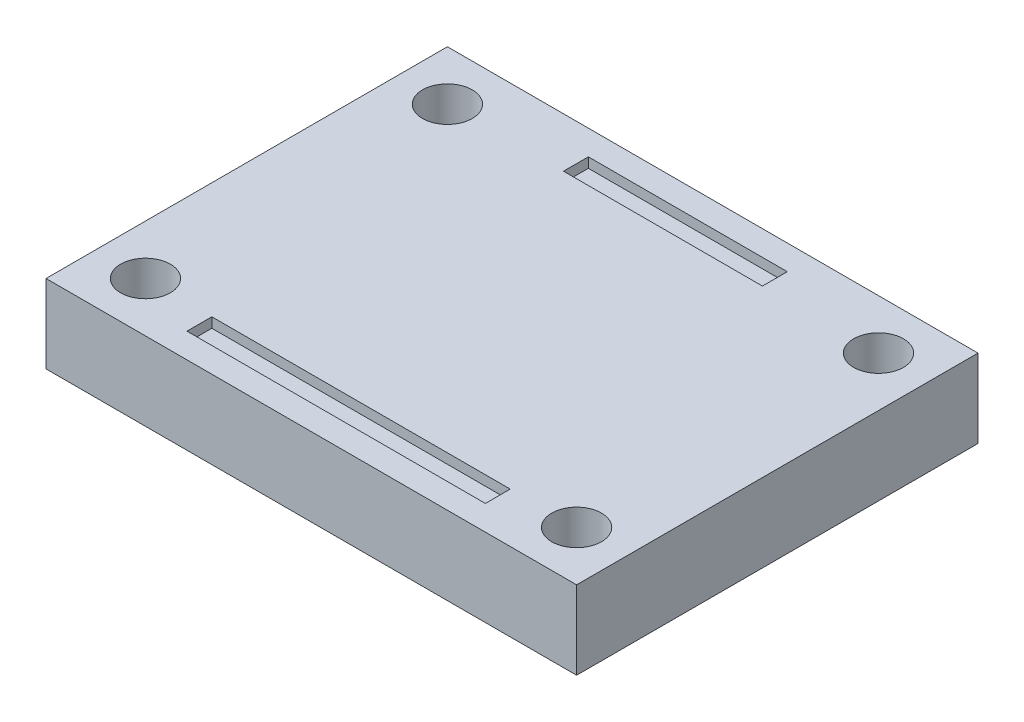
SolidWorks part; units mm, degrees
ref_plane "Front Plane" through (0, 0, 0) normal (0, 0, 1) x (1, 0, 0)
ref_plane "Top Plane" through (0, 0, 0) normal (0, 1, 0) x (1, 0, 0)
ref_plane "Right Plane" through (0, 0, 0) normal (1, 0, 0) x (0, 0, -1)
sketch "Sketch1" plane through (0, 0, 0) normal (0, 1, 0) x (1, 0, 0)
  line L0 (0, 0) -> (0, 20.5)
  line L1 (0, 0) -> (27.1, 0)
  line L2 (0, 20.5) -> (27.1, 20.5)
  line L3 (27.1, 0) -> (27.1, 20.5)
  dimension "D1" = 27.1
  dimension "D2" = 20.5
extrude "Boss-Extrude1" add sketch "Sketch1" along normal blind 4 contours L1 L3 L2 L0
sketch "Sketch3" plane through (0, 4, 0) normal (0, 1, 0) x (1, 0, 0)
  line L0 (0, 0) -> (0, 20.5) construction
  line L1 (13.55, 28.5431) -> (13.55, -9.9219) construction
  line L2 (-7.4225, 10.25) -> (32.0223, 10.25) construction
  line L3 (0, 20.5) -> (27.1, 20.5) construction
  circle A0 centre (2.54, 17.96) radius 1.27
  circle A1 centre (2.54, 2.54) radius 1.27
  circle A2 centre (24.56, 2.54) radius 1.27
  circle A3 centre (24.56, 17.96) radius 1.27
  dimension "D1" = 2.54
  dimension "D2" = 2.54
  dimension "D3" = 2.54
sketch "Sketch2" plane through (0, 4, 0) normal (0, 1, 0) x (1, 0, 0)
  line L0 (27.1, 0) -> (27.1, 20.5) construction
  line L1 (0, 20.5) -> (27.1, 20.5) construction
  line L2 (8.47, 19.23) -> (18.63, 19.23)
  line L3 (8.47, 19.23) -> (8.47, 17.96)
  line L4 (8.47, 17.96) -> (18.63, 17.96)
  line L5 (0, 0) -> (27.1, 0) construction
  line L6 (5.93, 2.54) -> (21.17, 2.54)
  line L7 (5.93, 2.54) -> (5.93, 1.27)
  line L8 (5.93, 1.27) -> (21.17, 1.27)
  line L10 (13.55, 23.6128) -> (13.55, -8.7709) construction
  line L11 (18.63, 19.23) -> (18.63, 17.96)
  line L12 (8.47, 19.23) -> (18.63, 17.96) construction
  line L13 (8.47, 17.96) -> (18.63, 19.23) construction
  line L15 (21.17, 2.54) -> (21.17, 1.27)
  line L16 (5.93, 2.54) -> (21.17, 1.27) construction
  line L17 (5.93, 1.27) -> (21.17, 2.54) construction
  point P0 (13.55, 18.595)
  point P4 (13.55, 1.905)
  dimension "D1" = 1.27
  dimension "D2" = 1.27
  dimension "D3" = 10.16
  dimension "D4" = 15.24
  dimension "D5" = 13.55
  dimension "D6" = 1.27
  dimension "D7" = 1.27
extrude "Cut-Extrude1" cut sketch "Sketch3" against normal through all contours A2
extrude "Cut-Extrude2" cut sketch "Sketch2" against normal blind 0.508
